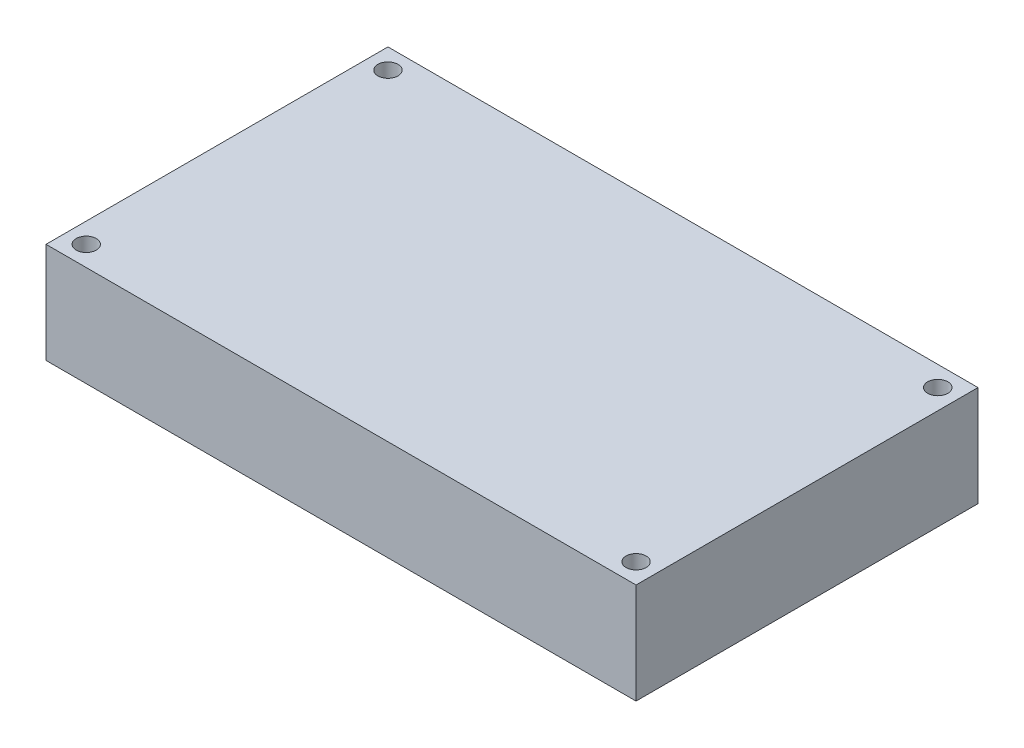
SolidWorks part; units mm, degrees
ref_plane "Alzado" through (0, 0, 0) normal (0, 0, 1) x (1, 0, 0)
ref_plane "Planta" through (0, 0, 0) normal (0, 1, 0) x (1, 0, 0)
ref_plane "Vista lateral" through (0, 0, 0) normal (1, 0, 0) x (0, 0, -1)
sketch "Croquis1" plane through (0, 0, 0) normal (0, 1, 0) x (1, 0, 0)
  line L1 (44, 25.5) -> (-44, 25.5)
  line L2 (44, 25.5) -> (44, -25.5)
  line L3 (44, -25.5) -> (-44, -25.5)
  line L4 (-44, 25.5) -> (-44, -25.5)
  line L5 (44, 25.5) -> (-44, -25.5) construction
  line L6 (44, -25.5) -> (-44, 25.5) construction
  point P0 (0, 0)
  dimension "D1" = 88
  dimension "D2" = 51
extrude "Saliente-Extruir1" add sketch "Croquis1" along normal blind 15
sketch "Croquis2" plane through (0, 15, 0) normal (0, 1, 0) x (1, 0, 0)
  line L4 (-44, 25.5) -> (-44, -25.5)
  line L5 (-44, -25.5) -> (44, -25.5)
  line L6 (44, -25.5) -> (44, 25.5)
  line L7 (44, 25.5) -> (-44, 25.5)
  line L8 (-44, 25.5) -> (-44, -25.5)
  line L9 (-44, -25.5) -> (44, -25.5)
  line L10 (44, -25.5) -> (44, 25.5)
  line L11 (44, 25.5) -> (-44, 25.5)
  dimension "D1" = 0
extrude "Saliente-Extruir2" [suppressed] add sketch "Croquis2" along normal blind 12.4
sketch "Croquis3" plane through (0, 0, 0) normal (0, -1, 0) x (1, 0, 0)
  line L0 (-44, 25.5) -> (44, 25.5) construction
  line L1 (41, -22.5) -> (-41, -22.5) construction
  line L2 (41, -22.5) -> (41, 22.5) construction
  line L3 (41, 22.5) -> (-41, 22.5) construction
  line L4 (-41, -22.5) -> (-41, 22.5) construction
  line L5 (41, -22.5) -> (-41, 22.5) construction
  line L6 (41, 22.5) -> (-41, -22.5) construction
  line L7 (-44, -25.5) -> (-44, 25.5) construction
  circle A0 centre (-41, 22.5) radius 1.5
  circle A1 centre (41, 22.5) radius 1.5
  circle A2 centre (41, -22.5) radius 1.5
  circle A3 centre (-41, -22.5) radius 1.5
  point P0 (0, 0)
  dimension "D3" = 3
  dimension "D1" = 3
  dimension "D2" = 3
extrude "Cortar-Extruir1" cut sketch "Croquis3" against normal through all
